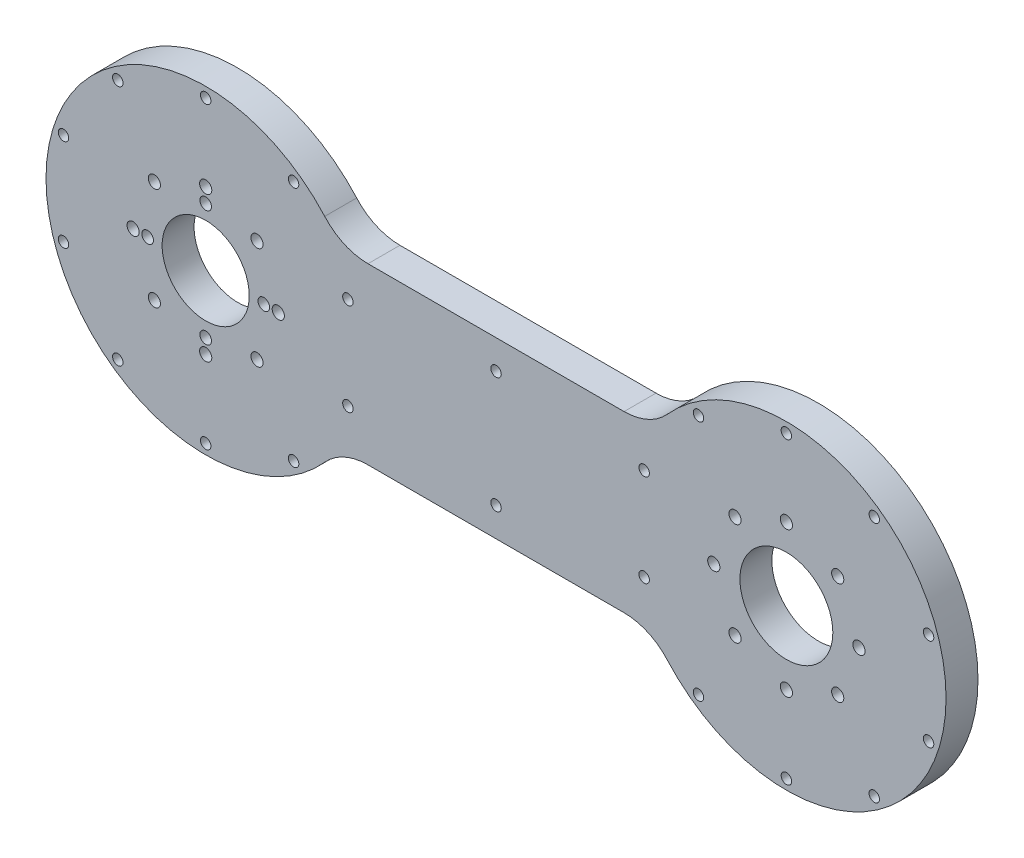
SolidWorks part; units mm, degrees
material "Delrin 2700 NC010, copolymère d'acétal à faible viscosité (SS)"
ref_plane "Plan de face" through (0, 0, 0) normal (0, 0, 1) x (1, 0, 0)
ref_plane "Plan de dessus" through (0, 0, 0) normal (0, 1, 0) x (1, 0, 0)
ref_plane "Plan de droite" through (0, 0, 0) normal (1, 0, 0) x (0, 0, -1)
sketch "Esquisse1" plane through (0, 0, 0) normal (0, 0, 1) x (1, 0, 0)
  line L0 (0, 0) -> (-200, 0) construction
  line L2 (60, 60) -> (-260, 60)
  line L3 (60, 60) -> (60, -60)
  line L4 (60, -60) -> (-260, -60)
  line L5 (-260, 60) -> (-260, -60)
  line L6 (60, 60) -> (-260, -60) construction
  line L7 (60, -60) -> (-260, 60) construction
  circle A0 centre (0, 0) radius 16
  circle A1 centre (-200, 0) radius 15
  circle A2 centre (-200, 0) radius 20 construction
  circle A3 centre (-200, 20) radius 2
  circle A4 centre (-180, 0) radius 2
  circle A5 centre (-200, -20) radius 2
  circle A6 centre (-220, 0) radius 2
  point P8 (-100, 0)
  point P17 (-200, 0)
  dimension "D1" = 32
  dimension "D2" = 30
  dimension "D3" = 40
  dimension "D4" = 4
  dimension "D6" = 120
  dimension "D7" = 320
  dimension "D8" = 200
  dimension "D5" = 4
extrude "Boss.-Extru.1" add sketch "Esquisse1" along normal blind 11
sketch "Esquisse2" plane through (0, 0, 11) normal (0, 0, 1) x (1, 0, 0)
  circle A0 centre (-200, 0) radius 25 construction
  circle A1 centre (-200, 25) radius 2.1
  circle A2 centre (-182.3223, 17.6777) radius 2.1
  circle A3 centre (-200, 0) radius 25 construction
  circle A4 centre (-175, 0) radius 2.1
  circle A5 centre (-200, 0) radius 25 construction
  circle A6 centre (-182.3223, -17.6777) radius 2.1
  circle A7 centre (-200, 0) radius 25 construction
  circle A8 centre (-200, -25) radius 2.1
  circle A9 centre (-200, 0) radius 25 construction
  circle A10 centre (-217.6777, -17.6777) radius 2.1
  circle A11 centre (-200, 0) radius 25 construction
  circle A12 centre (-225, 0) radius 2.1
  circle A13 centre (-200, 0) radius 25 construction
  circle A14 centre (-217.6777, 17.6777) radius 2.1
  circle A15 centre (-200, 0) radius 25 construction
  circle A16 centre (0, 0) radius 25 construction
  circle A17 centre (0, 25) radius 2.1
  circle A18 centre (17.6777, 17.6777) radius 2.1
  circle A19 centre (25, 0) radius 2.1
  circle A20 centre (17.6777, -17.6777) radius 2.1
  circle A21 centre (0, -25) radius 2.1
  circle A22 centre (-17.6777, -17.6777) radius 2.1
  circle A23 centre (-25, 0) radius 2.1
  circle A24 centre (-17.6777, 17.6777) radius 2.1
  point P28 (-200, 0)
  point P48 (0, 0)
  dimension "D1" = 50
  dimension "D2" = 4.2
  dimension "D4" = 50
  dimension "D5" = 4.2
  dimension "D3" = 8
  dimension "D6" = 8
extrude "Enlèv. mat.-Extru.1" cut sketch "Esquisse2" against normal blind 11
sketch "Esquisse3" plane through (0, 0, 11) normal (0, 0, 1) x (1, 0, 0)
  line L0 (-200, 0) -> (0, 0) construction
  line L1 (-200, 30) -> (0, 30) construction
  line L2 (-200, -30) -> (0, -30) construction
  line L3 (-153.9023, 30) -> (-46.0977, 30)
  line L4 (-153.9023, -30) -> (-46.0977, -30)
  circle A0 centre (-200, 0) radius 55 construction
  circle A1 centre (0, 0) radius 55 construction
  arc A2 (-200, 30) -> (-200, -30) centre (-200, 0) ccw construction
  arc A3 (0, -30) -> (0, 30) centre (0, 0) ccw construction
  arc A4 (-153.9023, 30) -> (-153.9023, -30) centre (-200, 0) ccw
  arc A5 (-46.0977, 30) -> (-46.0977, -30) centre (0, 0) cw
  point P6 (-100, 0)
  point P14 (-40, 30)
  point P18 (-160, 30)
  point P20 (0, 0)
  point P21 (-160, -30)
  dimension "D2" = 110
  dimension "D3" = 110
  dimension "D1" = 60
extrude "Enlèv. mat.-Extru.2" cut sketch "Esquisse3" against normal through all flip side to cut
fillet "Congé1" radius 20 4 edges at (-46.0977, -30, 5.5) (-153.9023, -30, 5.5) (-46.0977, 30, 5.5) (-153.9023, 30, 5.5)
sketch "Esquisse4" plane through (0, 0, 11) normal (0, 0, 1) x (1, 0, 0)
  line L0 (-100, 30) -> (-100, -30) construction
  line L1 (-55.9017, 30) -> (-144.0983, 30) construction
  line L2 (-144.0983, -30) -> (-55.9017, -30) construction
  circle A1 centre (-200, 51.5) radius 1.8
  circle A2 centre (-169.7291, 41.6644) radius 1.8
  circle A4 centre (-151.0206, 15.9144) radius 1.8
  circle A6 centre (-151.0206, -15.9144) radius 1.8
  circle A7 centre (-200, 0) radius 51.5 construction
  circle A8 centre (-169.7291, -41.6644) radius 1.8
  circle A9 centre (-200, 0) radius 51.5 construction
  circle A10 centre (-200, -51.5) radius 1.8
  circle A11 centre (-200, 0) radius 51.5 construction
  circle A12 centre (-230.2709, -41.6644) radius 1.8
  circle A13 centre (-200, 0) radius 51.5 construction
  circle A14 centre (-248.9794, -15.9144) radius 1.8
  circle A15 centre (-200, 0) radius 51.5 construction
  circle A16 centre (-248.9794, 15.9144) radius 1.8
  circle A17 centre (-200, 0) radius 51.5 construction
  circle A18 centre (-230.2709, 41.6644) radius 1.8
  circle A19 centre (-200, 0) radius 51.5 construction
  circle A20 centre (0, 0) radius 51.5 construction
  circle A21 centre (0, 0) radius 51.5 construction
  circle A22 centre (0, 0) radius 51.5 construction
  circle A23 centre (0, 0) radius 51.5 construction
  circle A24 centre (0, 0) radius 51.5 construction
  circle A25 centre (0, 0) radius 51.5 construction
  circle A26 centre (0, 0) radius 51.5 construction
  circle A27 centre (0, 0) radius 51.5 construction
  circle A28 centre (0, 0) radius 51.5 construction
  circle A29 centre (0, 0) radius 51.5 construction
  circle A30 centre (30.2709, 41.6644) radius 1.8
  circle A31 centre (48.9794, 15.9144) radius 1.8
  circle A32 centre (48.9794, -15.9144) radius 1.8
  circle A33 centre (30.2709, -41.6644) radius 1.8
  circle A34 centre (0, -51.5) radius 1.8
  circle A35 centre (-30.2709, -41.6644) radius 1.8
  circle A36 centre (-48.9794, -15.9144) radius 1.8
  circle A37 centre (-48.9794, 15.9144) radius 1.8
  circle A38 centre (-30.2709, 41.6644) radius 1.8
  circle A39 centre (0, 51.5) radius 1.8
  point P41 (-200, 0)
  dimension "D2" = 3.6
  dimension "D3" = 10
extrude "Enlèv. mat.-Extru.3" cut sketch "Esquisse4" against normal through all
sketch "Esquisse5" plane through (0, 0, 11) normal (0, 0, 1) x (1, 0, 0)
  line L0 (-100, 30) -> (-100, -30) construction
  line L1 (-55.9017, 30) -> (-144.0983, 30) construction
  line L2 (-144.0983, -30) -> (-55.9017, -30) construction
  circle A0 centre (-100, 20) radius 1.8
  circle A1 centre (-100, -20) radius 1.8
  dimension "D1" = 3.6
  dimension "D3" = 3.6
  dimension "D2" = 10
  dimension "D4" = 10
extrude "Enlèv. mat.-Extru.4" cut sketch "Esquisse5" against normal through all
